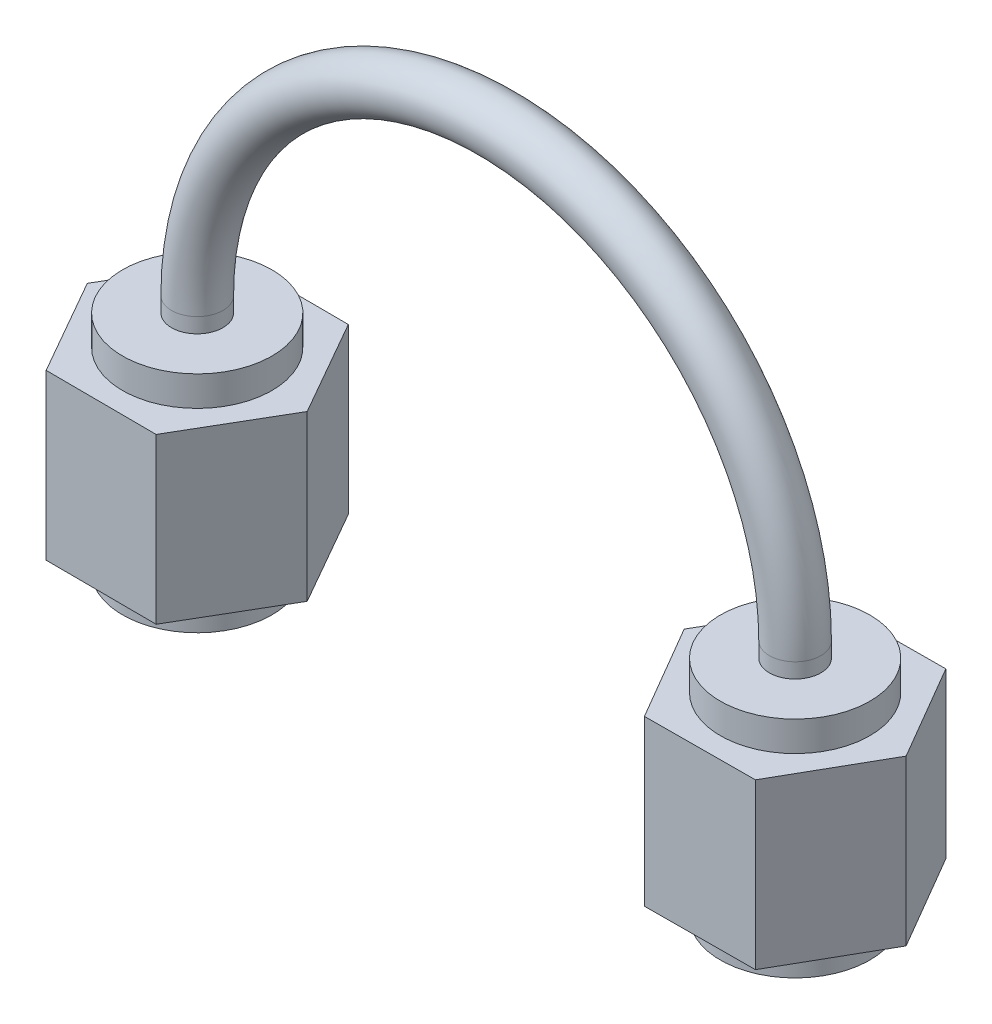
SolidWorks part; units mm, degrees
ref_plane "Front Plane" through (0, 0, 0) normal (0, 0, 1) x (1, 0, 0)
ref_plane "Top Plane" through (0, 0, 0) normal (0, 1, 0) x (1, 0, 0)
ref_plane "Right Plane" through (0, 0, 0) normal (1, 0, 0) x (0, 0, -1)
sketch "Sketch1" plane through (0, 0, 0) normal (0, 1, 0) x (1, 0, 0)
  line L0 (-12.7, 0) -> (12.7, 0) construction
  circle A0 centre (-12.7, 0) radius 3.175
  circle A1 centre (12.7, 0) radius 3.175
  dimension "D1" = 6.35
  dimension "D2" = 6.35
  dimension "D3" = 25.4
extrude "Boss-Extrude1" add sketch "Sketch1" along normal blind 9.525
sketch "Sketch2" plane through (0, 9.525, 0) normal (0, 1, 0) x (1, 0, 0)
  line L1 (-8.0073, -0.0217) -> (-10.3349, 4.0531)
  line L2 (-10.3349, 4.0531) -> (-15.0275, 4.0748)
  line L3 (-15.0275, 4.0748) -> (-17.3927, 0.0217)
  line L4 (-17.3927, 0.0217) -> (-15.0651, -4.0531)
  line L5 (-15.0651, -4.0531) -> (-10.3725, -4.0748)
  line L6 (-10.3725, -4.0748) -> (-8.0073, -0.0217)
  circle A0 centre (-12.7, 0) radius 4.064 construction
  point P1 (-10.3349, -4.064)
  dimension "D1" = 8.128
extrude "Boss-Extrude2" add sketch "Sketch2" against normal blind 6.985 from offset 1.27 offset against normal yes
mirror "Mirror1" about plane through (0, 0, 0) normal (1, 0, 0) of "Boss-Extrude2"
sketch "Sketch3" plane through (0, 0, 0) normal (0, 0, 1) x (1, 0, 0)
  line L0 (-12.7, 9.525) -> (-12.7, 10.16)
  line L1 (-9.525, 9.525) -> (-15.875, 9.525) construction
  line L2 (12.7, 9.525) -> (12.7, 10.16)
  line L3 (15.875, 9.525) -> (9.525, 9.525) construction
  arc A0 (-12.7, 10.16) -> (12.7, 10.16) centre (0, 10.16) cw
  dimension "D1" = 0.635
sketch "Sketch4" plane through (0, 9.525, 0) normal (0, 1, 0) x (1, 0, 0)
  circle A0 centre (-12.7, 0) radius 1.0922
  dimension "D1" = 2.1844
sweep "Sweep1" add profiles "Sketch4" path "Sketch3"
